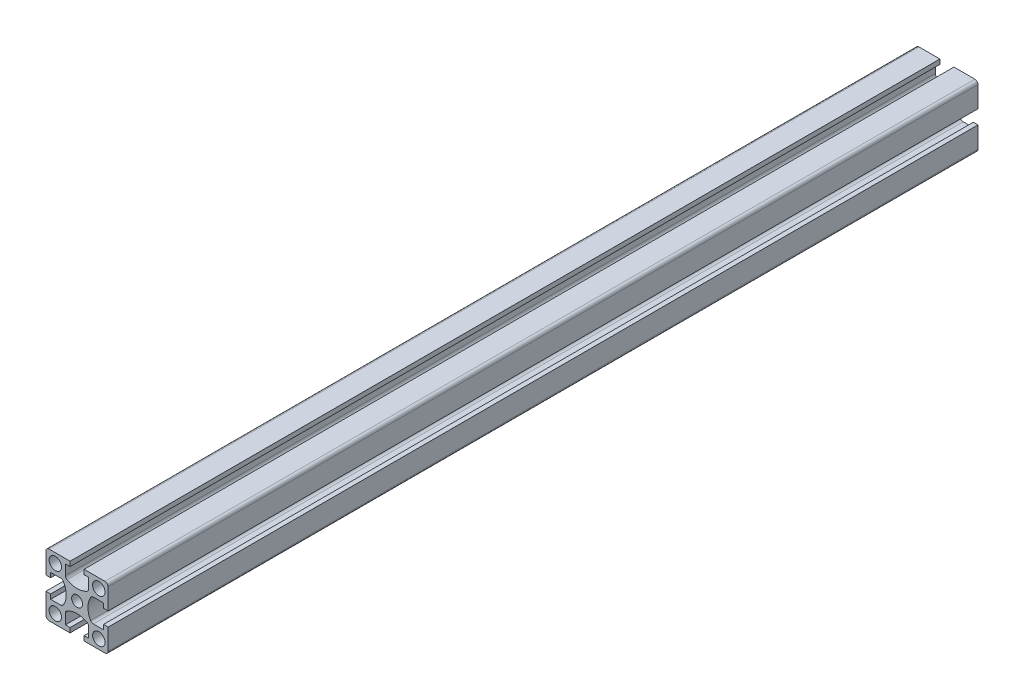
SolidWorks part; units mm, degrees
ref_plane "Front Plane" through (0, 0, 0) normal (0, 0, 1) x (1, 0, 0)
ref_plane "Top Plane" through (0, 0, 0) normal (0, 1, 0) x (1, 0, 0)
ref_plane "Right Plane" through (0, 0, 0) normal (1, 0, 0) x (0, 0, -1)
sketch "Sketch1" plane through (0, 0, 0) normal (0, 0, 1) x (1, 0, 0)
  line L64 (-12.5, 11.25) -> (-12.5, 2.8125)
  line L65 (-12.5, 2.8125) -> (-10.625, 2.8125)
  line L66 (-10.625, 2.8125) -> (-10.625, 4.6875)
  line L67 (-10.625, 4.6875) -> (-6.5461, 4.6875)
  line L68 (-6.5461, -4.6875) -> (-10.625, -4.6875)
  line L69 (-10.625, -4.6875) -> (-10.625, -2.8125)
  line L70 (-10.625, -2.8125) -> (-12.5, -2.8125)
  line L71 (-12.5, -2.8125) -> (-12.5, -11.25)
  line L72 (-11.25, -12.5) -> (-2.8125, -12.5)
  line L73 (-2.8125, -12.5) -> (-2.8125, -10.625)
  line L74 (-2.8125, -10.625) -> (-4.6875, -10.625)
  line L75 (-4.6875, -10.625) -> (-4.6875, -6.5461)
  line L76 (4.6875, -6.5461) -> (4.6875, -10.625)
  line L77 (4.6875, -10.625) -> (2.8125, -10.625)
  line L78 (2.8125, -10.625) -> (2.8125, -12.5)
  line L79 (2.8125, -12.5) -> (11.25, -12.5)
  line L80 (12.5, -11.25) -> (12.5, -2.8125)
  line L81 (12.5, -2.8125) -> (10.625, -2.8125)
  line L82 (10.625, -2.8125) -> (10.625, -4.6875)
  line L83 (10.625, -4.6875) -> (6.5461, -4.6875)
  line L84 (6.5461, 4.6875) -> (10.625, 4.6875)
  line L85 (10.625, 4.6875) -> (10.625, 2.8125)
  line L86 (10.625, 2.8125) -> (12.5, 2.8125)
  line L87 (12.5, 2.8125) -> (12.5, 11.25)
  line L88 (11.25, 12.5) -> (2.8125, 12.5)
  line L89 (2.8125, 12.5) -> (2.8125, 10.625)
  line L90 (2.8125, 10.625) -> (4.6875, 10.625)
  line L91 (4.6875, 10.625) -> (4.6875, 6.5461)
  line L92 (-4.6875, 6.5461) -> (-4.6875, 10.625)
  line L93 (-4.6875, 10.625) -> (-2.8125, 10.625)
  line L94 (-2.8125, 10.625) -> (-2.8125, 12.5)
  line L95 (-2.8125, 12.5) -> (-11.25, 12.5)
  circle A5 centre (-8.75, -8.75) radius 2.5
  circle A6 centre (8.75, -8.75) radius 2.5
  circle A7 centre (8.75, 8.75) radius 2.5
  circle A8 centre (0, 0) radius 2.1875
  circle A9 centre (-8.75, 8.75) radius 2.5
  arc A32 (-11.25, 12.5) -> (-12.5, 11.25) centre (-11.25, 11.25) ccw
  arc A33 (-5.4635, 4.0625) -> (-6.5461, 4.6875) centre (-6.5461, 3.4375) ccw
  arc A34 (-5.4635, -4.0625) -> (-5.4635, 4.0625) centre (-12.5, 0) ccw
  arc A35 (-6.5461, -4.6875) -> (-5.4635, -4.0625) centre (-6.5461, -3.4375) ccw
  arc A36 (-12.5, -11.25) -> (-11.25, -12.5) centre (-11.25, -11.25) ccw
  arc A37 (-4.0625, -5.4635) -> (-4.6875, -6.5461) centre (-3.4375, -6.5461) ccw
  arc A38 (4.0625, -5.4635) -> (-4.0625, -5.4635) centre (0, -12.5) ccw
  arc A39 (4.6875, -6.5461) -> (4.0625, -5.4635) centre (3.4375, -6.5461) ccw
  arc A40 (11.25, -12.5) -> (12.5, -11.25) centre (11.25, -11.25) ccw
  arc A41 (5.4635, -4.0625) -> (6.5461, -4.6875) centre (6.5461, -3.4375) ccw
  arc A42 (5.4635, 4.0625) -> (5.4635, -4.0625) centre (12.5, 0) ccw
  arc A43 (6.5461, 4.6875) -> (5.4635, 4.0625) centre (6.5461, 3.4375) ccw
  arc A44 (12.5, 11.25) -> (11.25, 12.5) centre (11.25, 11.25) ccw
  arc A45 (4.0625, 5.4635) -> (4.6875, 6.5461) centre (3.4375, 6.5461) ccw
  arc A46 (-4.0625, 5.4635) -> (4.0625, 5.4635) centre (0, 12.5) ccw
  arc A47 (-4.6875, 6.5461) -> (-4.0625, 5.4635) centre (-3.4375, 6.5461) ccw
extrude "Boss-Extrude1" add sketch "Sketch1" along normal blind 350
